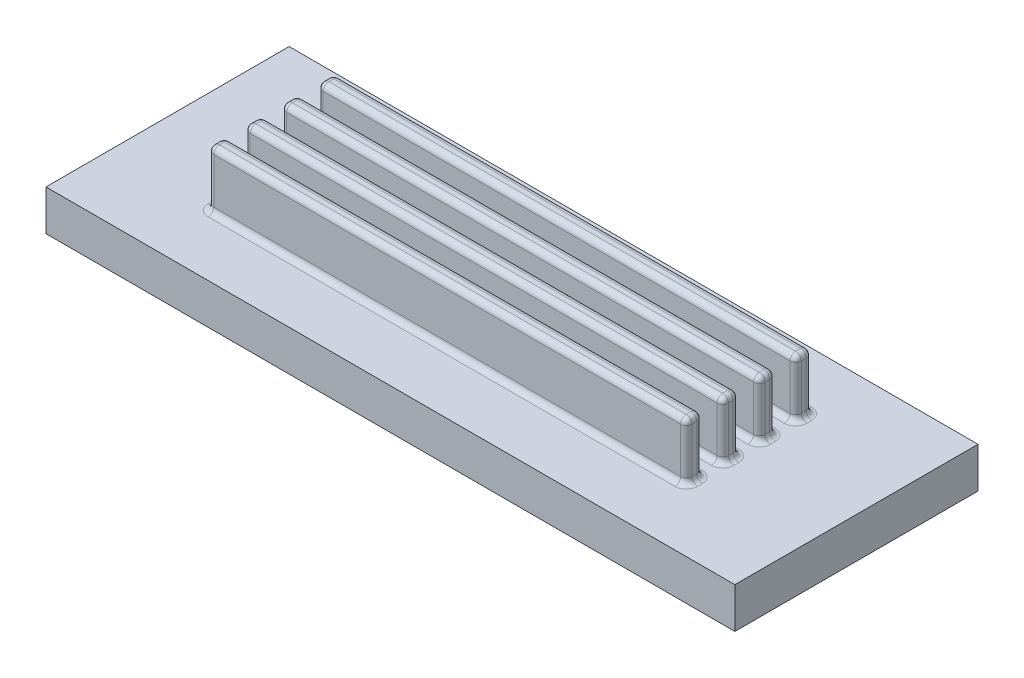
SolidWorks part; units mm, degrees
ref_plane "前视基准面" through (0, 0, 0) normal (0, 0, 1) x (1, 0, 0)
ref_plane "上视基准面" through (0, 0, 0) normal (0, 1, 0) x (1, 0, 0)
ref_plane "右视基准面" through (0, 0, 0) normal (1, 0, 0) x (0, 0, -1)
sketch "Sketch1" plane through (0, 0, 0) normal (0, 1, 0) x (1, 0, 0)
  line L1 (0, 0) -> (85, 0)
  line L2 (0, 0) -> (0, 30)
  line L3 (0, 30) -> (85, 30)
  line L4 (85, 0) -> (85, 30)
  dimension "D1" = 85
  dimension "D2" = 30
extrude "Boss-Extrude1" add sketch "Sketch1" along normal blind 5
sketch "Sketch2" plane through (0, 5, 0) normal (0, 1, 0) x (1, 0, 0)
  line L0 (85, 30) -> (0, 30) construction
  line L1 (12.5, 23) -> (71.5, 23)
  line L2 (12.5, 23) -> (12.5, 21)
  line L3 (12.5, 21) -> (71.5, 21)
  line L4 (71.5, 23) -> (71.5, 21)
  line L5 (0, 30) -> (0, 0) construction
  line L18 (12.5, 18.5) -> (71.5, 18.5)
  line L19 (12.5, 18.5) -> (12.5, 16.5)
  line L20 (12.5, 16.5) -> (71.5, 16.5)
  line L21 (71.5, 18.5) -> (71.5, 16.5)
  line L22 (12.5, 14) -> (71.5, 14)
  line L23 (12.5, 14) -> (12.5, 12)
  line L24 (12.5, 12) -> (71.5, 12)
  line L25 (71.5, 14) -> (71.5, 12)
  line L26 (12.5, 9.5) -> (71.5, 9.5)
  line L27 (12.5, 9.5) -> (12.5, 7.5)
  line L28 (12.5, 7.5) -> (71.5, 7.5)
  line L29 (71.5, 9.5) -> (71.5, 7.5)
  dimension "D1" = 7
  dimension "D2" = 2
  dimension "D3" = 4
  dimension "D9" = 12.5
  dimension "D10" = 59
extrude "Boss-Extrude2" add sketch "Sketch2" along normal blind 7
fillet "Fillet1" radius 0.7 48 edges at (12.5, 5, -22) (12.5, 8.5, -21) (42, 5, -21) (71.5, 8.5, -21) (71.5, 5, -22) (71.5, 8.5, -23) (12.5, 8.5, -23) (42, 5, -23) (42, 12, -23) (71.5, 12, -22) (42, 12, -21) (12.5, 12, -22) (12.5, 5, -17.5) (12.5, 8.5, -16.5) (42, 5, -16.5) (71.5, 8.5, -16.5) (71.5, 5, -17.5) (71.5, 8.5, -18.5) (12.5, 8.5, -18.5) (42, 5, -18.5) (42, 12, -18.5) (71.5, 12, -17.5) (42, 12, -16.5) (12.5, 12, -17.5) (12.5, 5, -13) (12.5, 8.5, -12) (42, 5, -12) (71.5, 8.5, -12) (71.5, 5, -13) (71.5, 8.5, -14) (12.5, 8.5, -14) (42, 5, -14) (42, 12, -14) (71.5, 12, -13) (42, 12, -12) (12.5, 12, -13) (12.5, 5, -8.5) (12.5, 8.5, -7.5) (42, 5, -7.5) (71.5, 8.5, -7.5) (71.5, 5, -8.5) (71.5, 8.5, -9.5) (12.5, 8.5, -9.5) (42, 5, -9.5) (42, 12, -9.5) (71.5, 12, -8.5) (42, 12, -7.5) (12.5, 12, -8.5)
